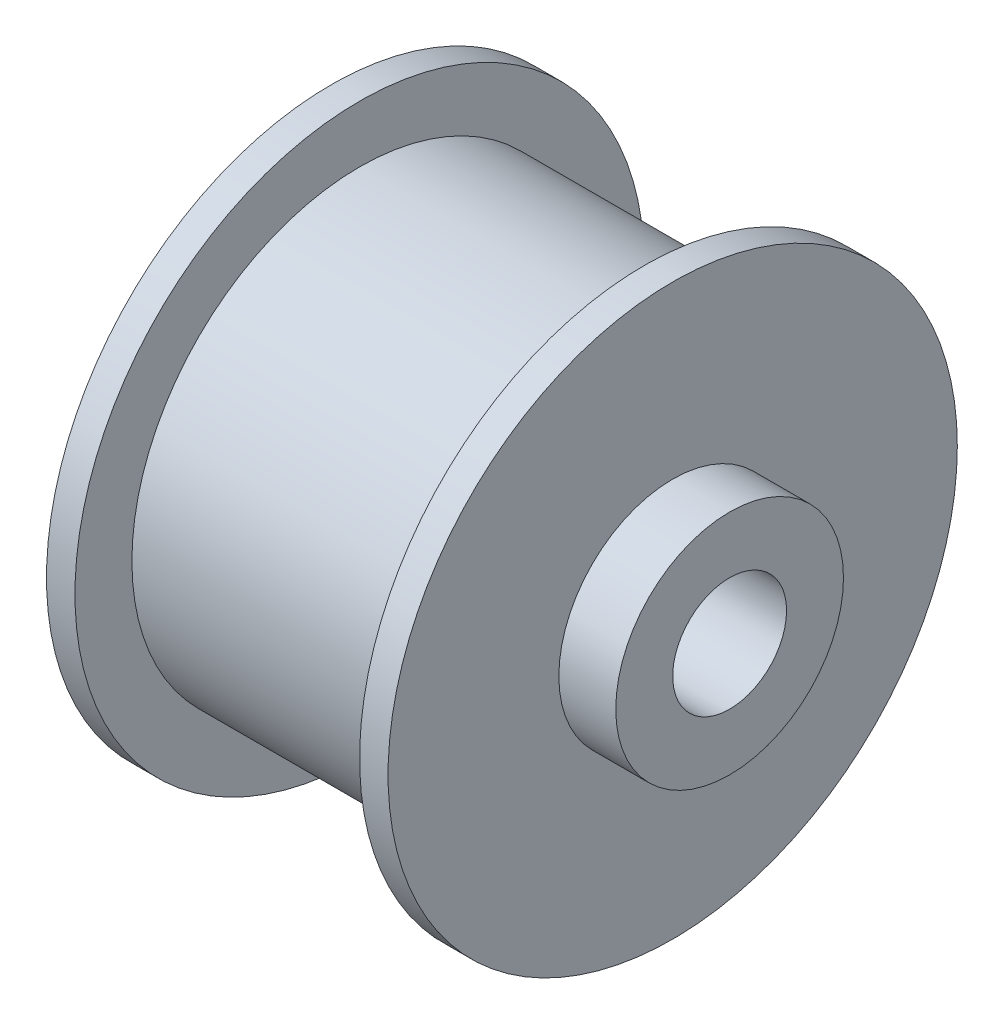
SolidWorks part; units mm, degrees
material "Plain Carbon Steel"
ref_plane "Front Plane" through (0, 0, 0) normal (0, 0, 1) x (1, 0, 0)
ref_plane "Top Plane" through (0, 0, 0) normal (0, 1, 0) x (1, 0, 0)
ref_plane "Right Plane" through (0, 0, 0) normal (1, 0, 0) x (0, 0, -1)
sketch "Sketch1" plane through (0, 0, 0) normal (0, 0, 1) x (1, 0, 0)
  line L0 (0, 10) -> (0, 25)
  line L1 (0, 25) -> (-2.5, 25)
  line L2 (-2.5, 25) -> (-2.5, 20)
  line L3 (-2.5, 20) -> (-27.5, 20)
  line L4 (-27.5, 20) -> (-27.5, 25)
  line L5 (-27.5, 25) -> (-30, 25)
  line L6 (-30, 25) -> (-30, 17.5)
  line L8 (5, 5) -> (5, 10)
  line L9 (5, 10) -> (0, 10)
  line L11 (-30, 5) -> (5, 5)
  line L12 (0, 0) -> (-44.4248, 0) construction
  line L13 (-30, 7.5) -> (-25, 7.5)
  line L14 (-25, 7.5) -> (-25, 17.5)
  line L15 (-25, 17.5) -> (-30, 17.5)
  line L16 (-30, 7.5) -> (-30, 5)
  dimension "D1" = 5
  dimension "D4" = 2.5
  dimension "D5" = 25
  dimension "D6" = 5
  dimension "D7" = 5
  dimension "D11" = 2.5
  dimension "D12" = 5
  dimension "D2" = 20
  dimension "D3" = 5
  dimension "D8" = 5
  dimension "D9" = 7.5
revolve "Revolve1" add sketch "Sketch1" angle 360 about L12
fillet "Fillet1" radius 1 1 edges at (-30, 0, -7.5)
equation "\"D6@Sketch1\"=\"D1@Sketch1\""
